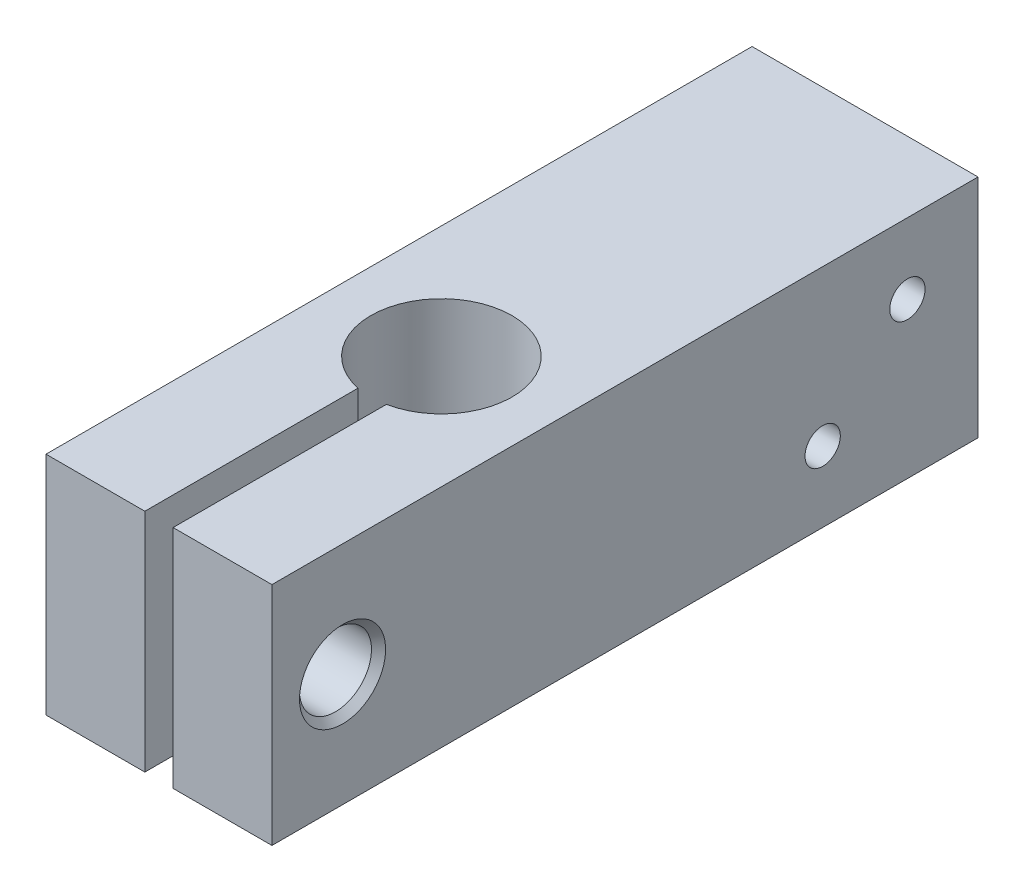
SolidWorks part; units mm, degrees
material "6063-T6"
ref_plane "Front Plane" through (0, 0, 0) normal (0, 0, 1) x (1, 0, 0)
ref_plane "Top Plane" through (0, 0, 0) normal (0, 1, 0) x (1, 0, 0)
ref_plane "Right Plane" through (0, 0, 0) normal (1, 0, 0) x (0, 0, -1)
sketch "Sketch1" plane through (0, 0, 0) normal (0, 0, 1) x (1, 0, 0)
  line L1 (8, -8) -> (-8, -8)
  line L2 (8, -8) -> (8, 8)
  line L3 (8, 8) -> (-8, 8)
  line L4 (-8, -8) -> (-8, 8)
  line L5 (8, -8) -> (-8, 8) construction
  line L6 (8, 8) -> (-8, -8) construction
  point P0 (0, 0)
  dimension "D1" = 16
  dimension "D2" = 16
extrude "Base" add sketch "Sketch1" along normal blind 50
sketch "Sketch2" plane through (0, 8, 0) normal (0, 1, 0) x (1, 0, 0)
  line L0 (-1, -50) -> (-1, -34.899)
  line L1 (8, -50) -> (-8, -50) construction
  line L2 (1, -50) -> (1, -34.899)
  line L3 (0, 0) -> (0, -9.2456) construction
  circle A0 centre (0, -30) radius 5
  line M6 (-8, -50) -> (8, -50)
  dimension "D1" = 10
  dimension "D2" = 20
  dimension "D3" = 2
extrude "RodSlot" cut sketch "Sketch2" against normal through all contours A0 | A0 L0 L2 M6
sketch "Sketch3" plane through (8, 0, 0) normal (1, 0, 0) x (0, 0, -1)
  line L0 (-50, -8) -> (-50, 8) construction
  circle A0 centre (-45, 0) radius 2.55
  dimension "D1" = 5.1
  dimension "D2" = 5
extrude "RodScrewMount" cut sketch "Sketch3" against normal up to next
chamfer "ChamferForRodScrew" distance 0.5 angle 45 1 edges at (8, 0, 42.45)
hole_wizard "M5x0.8 Tapped Hole for rod screw" positions "Sketch4" profile "Sketch5" tap size "M5x0.8" standard "ANSI Metric"
sketch "Sketch4" plane through (-8, 0, 0) normal (-1, 0, 0) x (0, 0, 1)
  point P0 (45, 0)
cosmetic thread "Hole Thread1" parameters "D1"=3.8, "D2"=5
sketch "Sketch5" plane through (-8, 0, 45) normal (0, 1, 0) x (0, 0, 1)
  line L0 (0, 0) -> (0, 8.9)
  line L1 (0, 8.9) -> (2.1, 7.6382)
  line L2 (2.1, 7.6382) -> (2.1, 0)
  line L5 (2.1, 0) -> (0, 0)
  line L10 (0, 8.9) -> (-2.1, 7.6382) construction
  line L11 (0, -6.35) -> (0, 107.95) construction
  dimension "Tap Drill Dia." = 4.2
  dimension "Tap Drill Depth" = 8.9
  dimension "Drill Angle" = 118
hole_wizard "M3x0.5 Tapped Hole for mount with second part" positions "Sketch7" profile "Sketch8" tap size "M3x0.5" standard "ANSI Metric" end condition through all
sketch "Sketch7" plane through (-8, 0, 0) normal (-1, 0, 0) x (0, 0, 1)
  line L1 (0, 8) -> (16, -8) construction
  line L2 (50, -8) -> (0, -8) construction
  line L3 (16, -8) -> (0, -8) construction
  line L5 (0, 8) -> (0, -8) construction
  line L6 (0, 0) -> (4.2163, 0) construction
  point P0 (5, 3)
  point P3 (11, -3)
  dimension "D1" = 3
  dimension "D2" = 3
sketch "Sketch8" plane through (-8, 3, 5) normal (0, 1, 0) x (0, 0, 1)
  line L0 (0, 0) -> (0, 16)
  line L1 (0, 16) -> (1.25, 16)
  line L2 (1.25, 16) -> (1.25, 0)
  line L5 (1.25, 0) -> (0, 0)
  line L11 (0, -6.35) -> (0, 107.95) construction
  dimension "Thru Tap Drill Dia." = 2.5
  dimension "Thru Tap Drill Depth" = 16
cosmetic thread "Hole Thread2" parameters "D2"=3
cosmetic thread "Hole Thread3" parameters "D2"=3
equation "\"D2@Sketch1\"=\"D1@Sketch1\""
equation "\"BaseDim\"= \"D2@Sketch1\""
